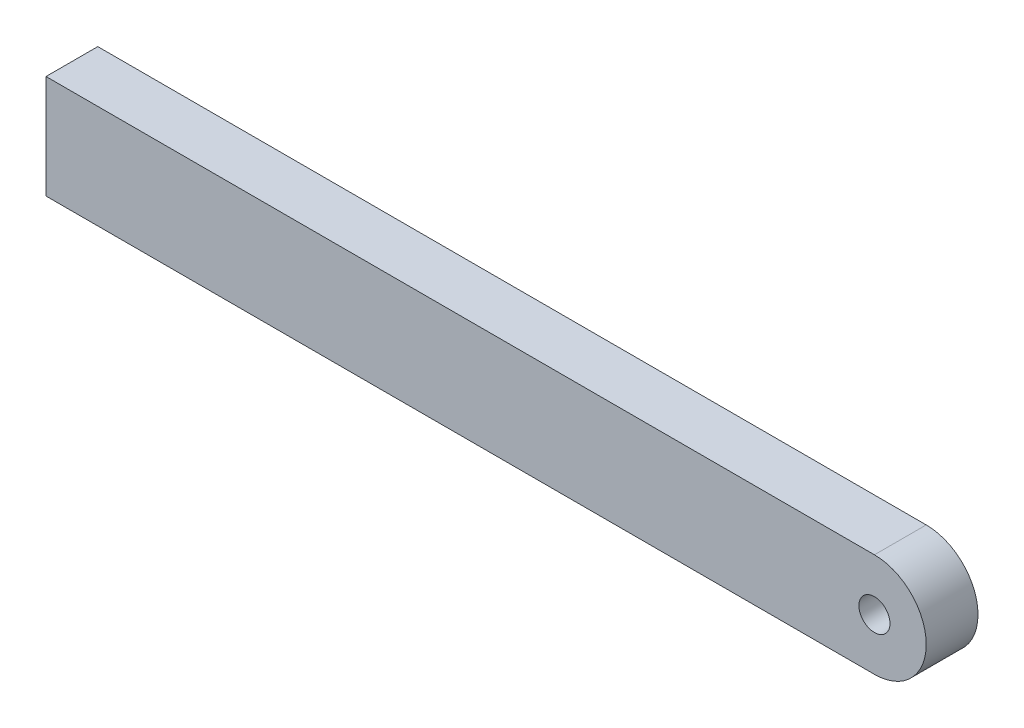
SolidWorks part; units mm, degrees
ref_plane "前视基准面" through (0, 0, 0) normal (0, 0, 1) x (1, 0, 0)
ref_plane "上视基准面" through (0, 0, 0) normal (0, 1, 0) x (1, 0, 0)
ref_plane "右视基准面" through (0, 0, 0) normal (1, 0, 0) x (0, 0, -1)
sketch "草图1" plane through (0, 0, 0) normal (0, 0, 1) x (1, 0, 0)
  line L1 (-40, -5) -> (40, -5)
  line L2 (-40, -5) -> (-40, 5)
  line L3 (-40, 5) -> (40, 5)
  line L5 (-40, -5) -> (40, 5) construction
  line L6 (-40, 5) -> (40, -5) construction
  arc A0 (40, -5) -> (40, 5) centre (40, 0) ccw
  circle A1 centre (40, 0) radius 1.5
  point P0 (0, 0)
  dimension "D3" = 3
  dimension "D1" = 10
  dimension "D2" = 80
extrude "凸台-拉伸1" add sketch "草图1" along normal blind 5
